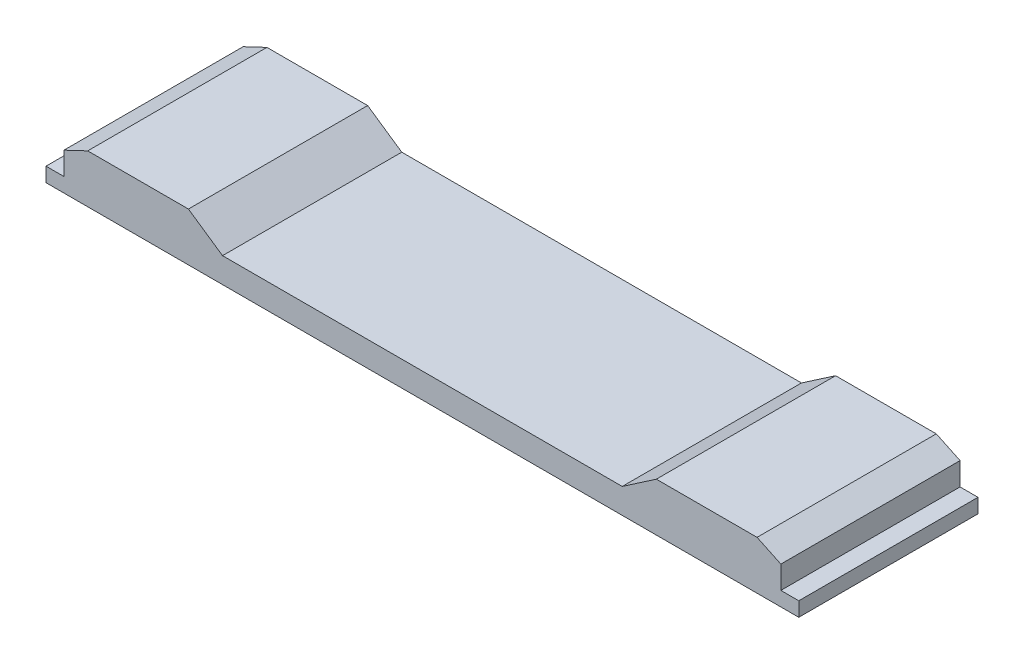
SolidWorks part; units mm, degrees
ref_plane "Спереди" through (0, 0, 0) normal (0, 0, 1) x (1, 0, 0)
ref_plane "Сверху" through (0, 0, 0) normal (0, 1, 0) x (1, 0, 0)
ref_plane "Справа" through (0, 0, 0) normal (1, 0, 0) x (0, 0, -1)
sketch "Эскиз1" plane through (0, 0, 0) normal (0, 0, 1) x (1, 0, 0)
  line L0 (0, 27.73) -> (0, 26.33) construction
  line L1 (20, 26.33) -> (21, 26.33)
  line L2 (-20, 27.13) -> (-20, 28.403)
  line L3 (20, 27.13) -> (21, 27.13)
  line L4 (21, 26.33) -> (21, 27.13)
  line L5 (-21, 26.33) -> (-21, 27.13)
  line L6 (-20, 27.13) -> (-21, 27.13)
  line L7 (-20, 26.33) -> (-21, 26.33)
  line L8 (-20, 28.403) -> (-18.6735, 29.032)
  line L9 (-18.6735, 29.032) -> (-13.0537, 29.032)
  line L10 (-13.0537, 29.032) -> (-11.1508, 27.73)
  line L11 (-11.1508, 27.73) -> (11.1508, 27.73)
  line L12 (11.1508, 27.73) -> (13.0537, 29.032)
  line L13 (13.0537, 29.032) -> (18.6735, 29.032)
  line L14 (18.6735, 29.032) -> (20, 28.403)
  line L15 (-11.1508, 27.73) -> (-13.0537, 29.032) construction
  line L16 (-18.6735, 29.032) -> (-20.3, 28.2607) construction
  line L17 (20.3, 28.2607) -> (18.6735, 29.032) construction
  line L28 (-20, 26.33) -> (20, 26.33)
  line L31 (20, 27.13) -> (20, 28.403)
  point P1 (0, 26.33)
  point P33 (0, 51.6036)
  dimension "D3" = 0.8
  dimension "D1" = 40
  dimension "D2" = 1.4
  dimension "D4" = 1
extrude "Бобышка-Вытянуть1" add sketch "Эскиз1" along normal blind 10
